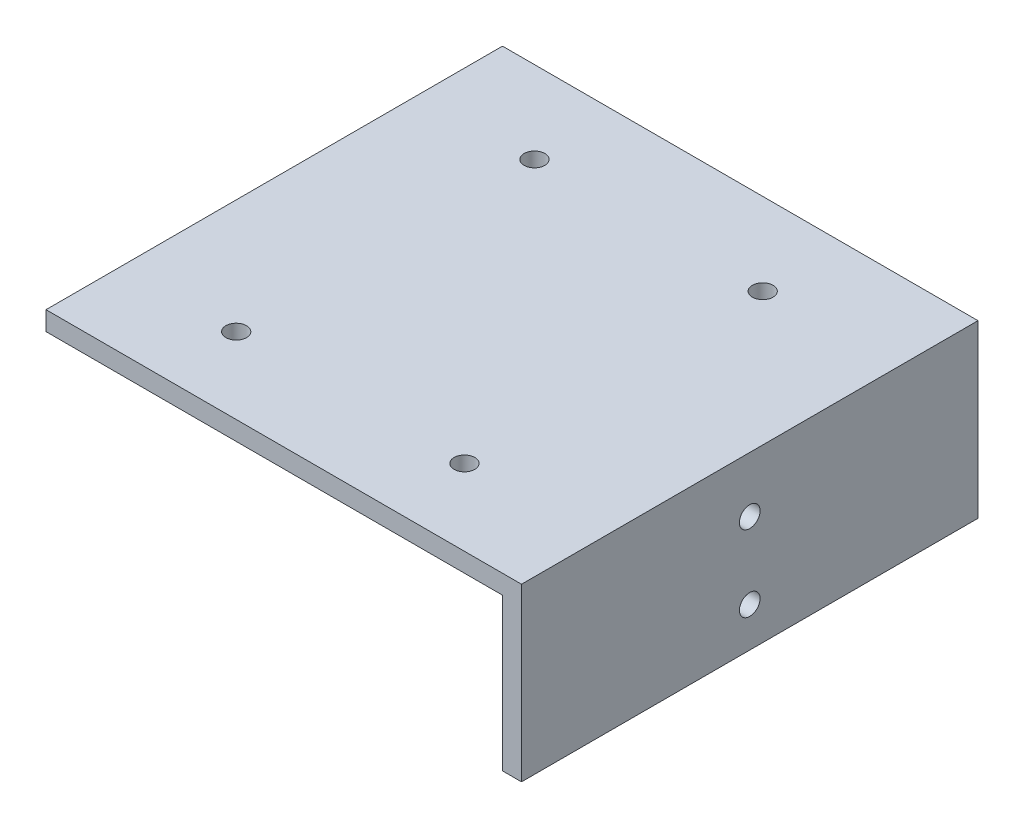
SolidWorks part; units mm, degrees
ref_plane "Front Plane" through (0, 0, 0) normal (0, 0, 1) x (1, 0, 0)
ref_plane "Top Plane" through (0, 0, 0) normal (0, 1, 0) x (1, 0, 0)
ref_plane "Right Plane" through (0, 0, 0) normal (1, 0, 0) x (0, 0, -1)
sketch "Sketch1" plane through (0, 0, 0) normal (0, 0, 1) x (1, 0, 0)
  line L0 (0, 0) -> (0, 28.575)
  line L1 (0, 28.575) -> (-79.375, 28.575)
  line L2 (-79.375, 28.575) -> (-79.375, 25.4)
  line L3 (-79.375, 25.4) -> (-3.175, 25.4)
  line L4 (-3.175, 25.4) -> (-3.175, 0)
  line L5 (-3.175, 0) -> (0, 0)
  dimension "D1" = 76.2
  dimension "D2" = 3.175
  dimension "D3" = 3.175
  dimension "D4" = 28.575
extrude "Boss-Extrude1" add sketch "Sketch1" along normal blind 76.2
hole_wizard "Tap Drill for #8-36 Tap1" positions "Sketch3" profile "Sketch2" hole size "#8-36" standard "ANSI Inch" end condition up to next
sketch "Sketch3" plane through (-3.175, 0, 0) normal (-1, 0, 0) x (0, 0, 1)
  point P0 (38.1, 6.6)
  point P3 (38.1, 19.3)
sketch "Sketch2" plane through (-3.175, 6.6, 38.1) normal (0, 1, 0) x (0, 0, 1)
  line L0 (0, 0) -> (0, 3.175)
  line L1 (0, 3.175) -> (1.7272, 3.175)
  line L2 (1.7272, 3.175) -> (1.7272, 0)
  line L5 (1.7272, 0) -> (0, 0)
  line L11 (0, -6.35) -> (0, 107.95) construction
  dimension "Thru Hole Dia." = 3.4544
  dimension "Thru Hole Depth" = 3.175
hole_wizard "Tap Drill for #8-36 Tap2" positions "Sketch5" profile "Sketch4" hole size "#8-36" standard "ANSI Inch" end condition up to next
sketch "Sketch5" plane through (0, 25.4, 0) normal (0, -1, 0) x (-1, 0, 0)
  line L0 (79.375, -76.2) -> (3.175, -76.2) construction
  line L1 (79.375, -76.2) -> (79.375, 0) construction
  point P0 (60.325, -63.5)
  point P2 (22.225, -63.5)
  point P4 (60.325, -13.7116)
  point P6 (22.225, -13.7116)
  dimension "D1" = 38.1
  dimension "D2" = 12.7
  dimension "D3" = 19.05
sketch "Sketch4" plane through (-60.325, 25.4, 63.5) normal (1, 0, 0) x (0, 0, -1)
  line L0 (0, 0) -> (0, 3.175)
  line L1 (0, 3.175) -> (1.7272, 3.175)
  line L2 (1.7272, 3.175) -> (1.7272, 0)
  line L5 (1.7272, 0) -> (0, 0)
  line L11 (0, -6.35) -> (0, 107.95) construction
  dimension "Thru Hole Dia." = 3.4544
  dimension "Thru Hole Depth" = 3.175
